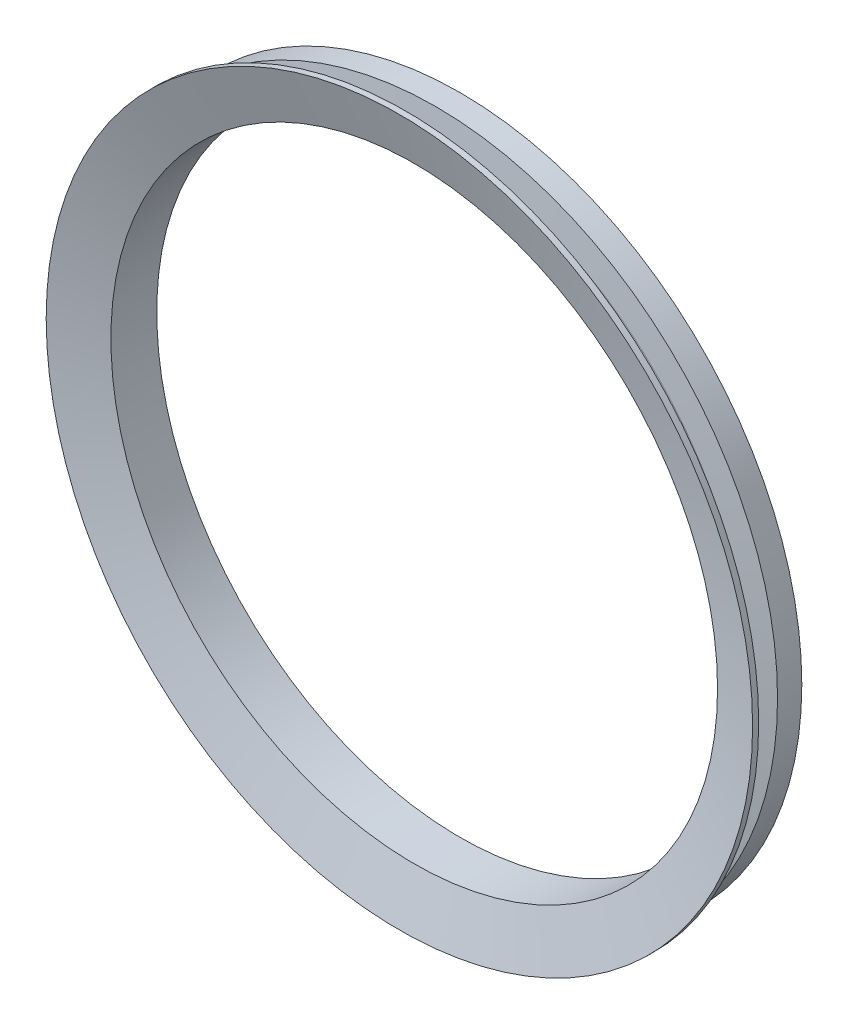
SolidWorks part; units mm, degrees
material "Nitrile Rubber"
ref_plane "Front Plane" through (0, 0, 0) normal (0, 0, 1) x (1, 0, 0)
ref_plane "Top Plane" through (0, 0, 0) normal (0, 1, 0) x (1, 0, 0)
ref_plane "Right Plane" through (0, 0, 0) normal (1, 0, 0) x (0, 0, -1)
sketch "Sketch1" plane through (0, 0, 0) normal (1, 0, 0) x (0, 0, -1)
  line L0 (0, 0) -> (80.2615, 0) construction
  line L2 (-9, 52.4) -> (-8.1, 52.4)
  line L3 (-8.1, 52.4) -> (-5.9616, 46.6383)
  line L4 (-4.0304, 46.8744) -> (-3.6, 50.7)
  line L5 (-3.6, 50.7) -> (0, 50.7)
  line L6 (0, 50.7) -> (0, 45)
  line L7 (0, 45) -> (-6.8, 45)
  line L8 (-9, 52.4) -> (-6.8, 45)
  arc A0 (-5.9616, 46.6383) -> (-4.0304, 46.8744) centre (-5.0241, 46.9862) ccw
  point P12 (-4.5, 42.7)
  dimension "D7" = 1
  dimension "D1" = 8
  dimension "D2" = 3.6
  dimension "D3" = 9
  dimension "D4" = 5.7
  dimension "D5" = 1.7
  dimension "D6" = 4.5
  dimension "D9" = 90
  dimension "D10" = 6.8
  dimension "D11" = 0.9
revolve "Revolve1" add sketch "Sketch1" angle 360 about L0
